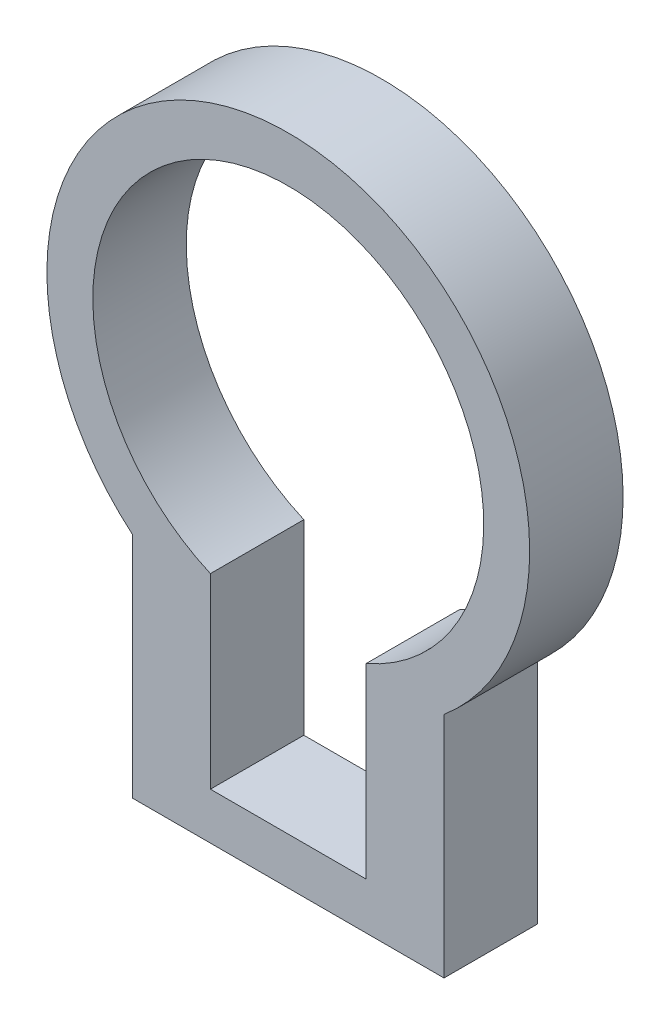
SolidWorks part; units mm, degrees
ref_plane "Plan de face" through (0, 0, 0) normal (0, 0, 1) x (1, 0, 0)
ref_plane "Plan de dessus" through (0, 0, 0) normal (0, 1, 0) x (1, 0, 0)
ref_plane "Plan de droite" through (0, 0, 0) normal (1, 0, 0) x (0, 0, -1)
sketch "Esquisse1" plane through (0, 0, 0) normal (0, 0, 1) x (1, 0, 0)
  line L1 (10, -8.5) -> (-10, -8.5)
  line L2 (10, -8.5) -> (10, 8.5)
  line L3 (10, 8.5) -> (-10, 8.5)
  line L4 (-10, -8.5) -> (-10, 8.5)
  line L5 (10, -8.5) -> (-10, 8.5) construction
  line L6 (10, 8.5) -> (-10, -8.5) construction
  point P0 (0, 0)
extrude "Boss.-Extru.1" add sketch "Esquisse1" along normal blind 6
sketch "Esquisse2" plane through (0, 0, 6) normal (0, 0, 1) x (1, 0, 0)
  circle A0 centre (0, 18) radius 15.5
extrude "Boss.-Extru.2" add sketch "Esquisse2" against normal blind 6
sketch "Esquisse3" plane through (0, 0, 6) normal (0, 0, 1) x (1, 0, 0)
  circle A0 centre (0, 18) radius 12.55
extrude "Enlèv. mat.-Extru.1" cut sketch "Esquisse3" against normal blind 6
sketch "Esquisse4" plane through (0, 0, 6) normal (0, 0, 1) x (1, 0, 0)
  line L0 (-10, -8.5) -> (10, -8.5) construction
  line L1 (-5, 6.489) -> (5, 6.489)
  line L2 (-5, 6.489) -> (-5, -5.5)
  line L3 (-5, -5.5) -> (5, -5.5)
  line L4 (5, 6.489) -> (5, -5.5)
  line L5 (-10, 6.1573) -> (-10, -8.5) construction
  line L6 (10, -8.5) -> (10, 6.1573) construction
  circle A0 centre (0, 18) radius 12.55 construction
  dimension "D1" = 3
  dimension "D2" = 5
  dimension "D3" = 5
extrude "Enlèv. mat.-Extru.2" cut sketch "Esquisse4" against normal blind 10
